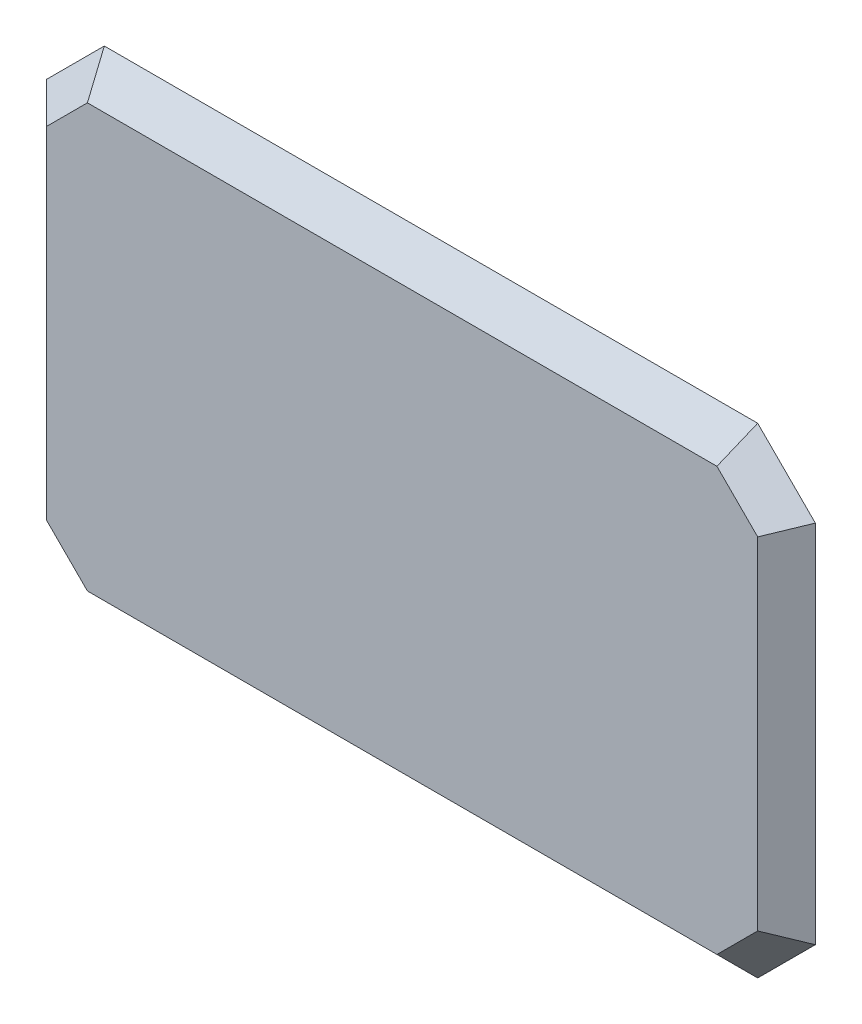
SolidWorks part; units mm, degrees
ref_plane "Front Plane" through (0, 0, 0) normal (0, 0, 1) x (1, 0, 0)
ref_plane "Top Plane" through (0, 0, 0) normal (0, 1, 0) x (1, 0, 0)
ref_plane "Right Plane" through (0, 0, 0) normal (1, 0, 0) x (0, 0, -1)
sketch "Sketch1" plane through (0, 0, 0) normal (0, 0, 1) x (1, 0, 0)
  line L0 (-78, -50) -> (58, -50)
  line L1 (58, -50) -> (70, -38)
  line L2 (70, -38) -> (70, 38)
  line L3 (70, 38) -> (58, 50)
  line L4 (58, 50) -> (-78, 50)
  line L5 (-78, 50) -> (-90, 38)
  line L6 (-90, 38) -> (-90, -38)
  line L7 (-90, -38) -> (-78, -50)
extrude "Sloped_45deg_Roof_Flat_Webcam_Top" add sketch "Sketch1" along normal blind 6 draft 45 from offset 0
